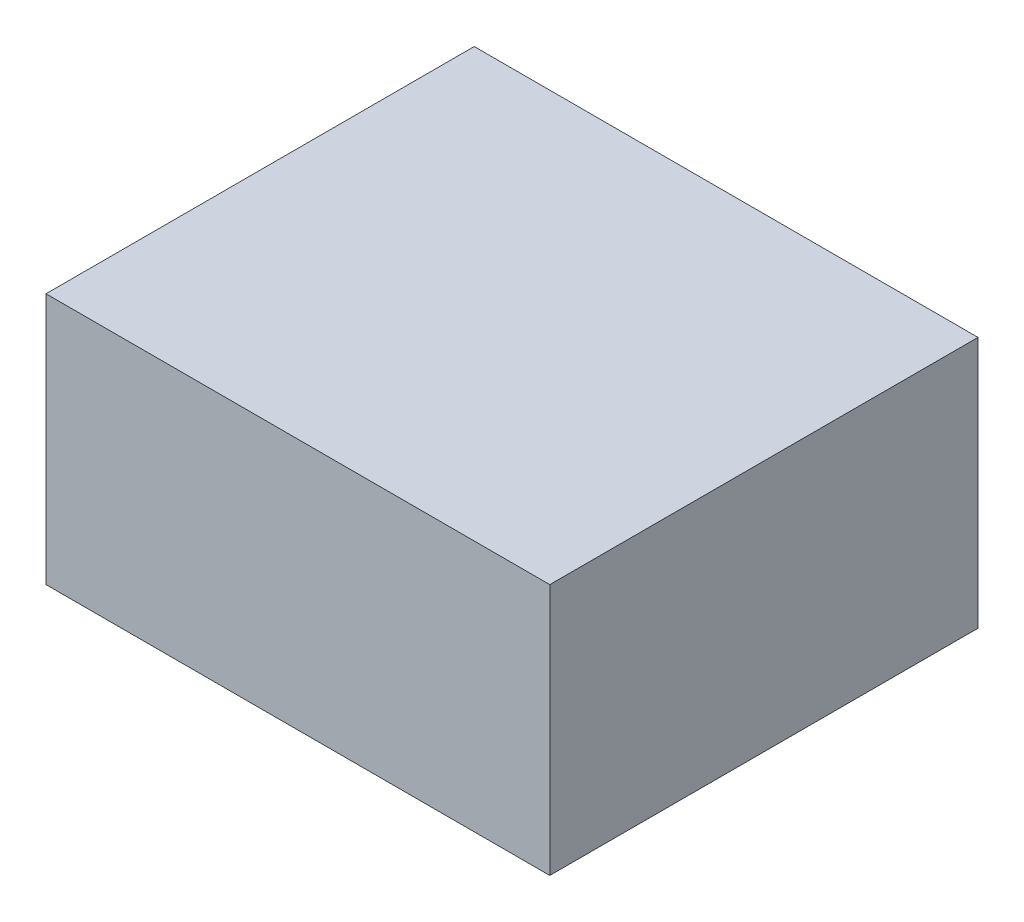
SolidWorks part; units mm, degrees
ref_plane "Front Plane" through (0, 0, 0) normal (0, 0, 1) x (1, 0, 0)
ref_plane "Top Plane" through (0, 0, 0) normal (0, 1, 0) x (1, 0, 0)
ref_plane "Right Plane" through (0, 0, 0) normal (1, 0, 0) x (0, 0, -1)
sketch "Sketch1" plane through (0, 0, 0) normal (0, 0, 1) x (1, 0, 0)
  line L1 (0, 0) -> (20, 0)
  line L2 (0, 0) -> (0, 10)
  line L3 (0, 10) -> (20, 10)
  line L4 (20, 0) -> (20, 10)
extrude "Boss-Extrude1" add sketch "Sketch1" along normal blind 5 and the other way blind 12
